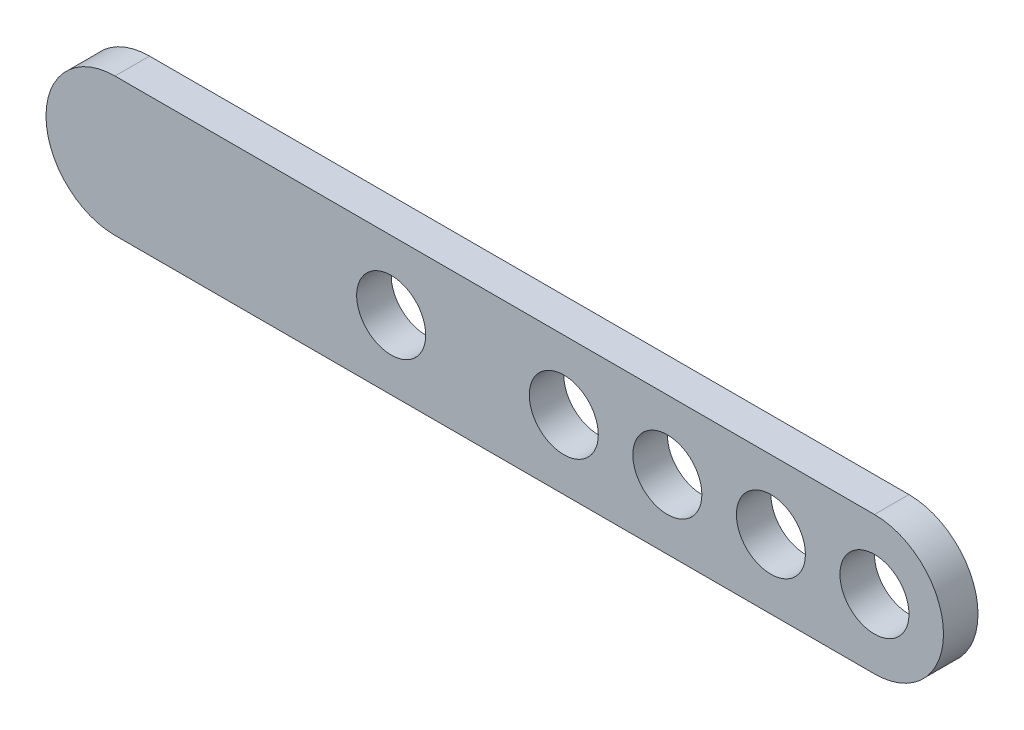
SolidWorks part; units mm, degrees
ref_plane "Front Plane" through (0, 0, 0) normal (0, 0, 1) x (1, 0, 0)
ref_plane "Top Plane" through (0, 0, 0) normal (0, 1, 0) x (1, 0, 0)
ref_plane "Right Plane" through (0, 0, 0) normal (1, 0, 0) x (0, 0, -1)
sketch "Sketch1" plane through (0, 0, 0) normal (0, 0, 1) x (1, 0, 0)
  line L0 (-88.9, 0) -> (88.9, 0) construction
  line L3 (-88.9, 25.4) -> (-88.9, -25.4) construction
  line L4 (-88.9, 25.4) -> (88.9, 25.4) construction
  line L7 (-88.9, -25.4) -> (88.9, -25.4) construction
  line L8 (-88.9, 25.4) -> (88.9, 25.4)
  line L9 (-88.9, -25.4) -> (88.9, -25.4)
  line L10 (-88.9, 25.4) -> (-190.5, 25.4)
  line L11 (-88.9, -25.4) -> (-190.5, -25.4)
  circle A0 centre (-88.9, 0) radius 12.7
  circle A1 centre (88.9, 0) radius 12.7
  arc A9 (88.9, 25.4) -> (88.9, -25.4) centre (88.9, 0) cw
  circle A10 centre (50.8, 0) radius 12.7
  circle A11 centre (12.7, 0) radius 12.7
  circle A12 centre (-25.4, 0) radius 12.7
  arc A13 (-190.5, 25.4) -> (-190.5, -25.4) centre (-190.5, 0) ccw
  point P3 (0, 0)
  point P6 (0, 0)
  point P9 (0, 0)
  point P10 (0, 0)
  point P14 (-88.9, 0)
  dimension "D2" = 25.4
  dimension "D3" = 25.4
  dimension "D6" = 4
  dimension "D5" = 177.8
  dimension "D7" = 38.1
  dimension "D1" = 177.8
  dimension "D4" = 50.8
  dimension "D8" = 101.6
extrude "Boss-Extrude1" add sketch "Sketch1" along normal blind 12.7
equation "\"CrankWidth\"=0.5"
equation "\"D1@Boss-Extrude1\"=\"CrankWidth\""
